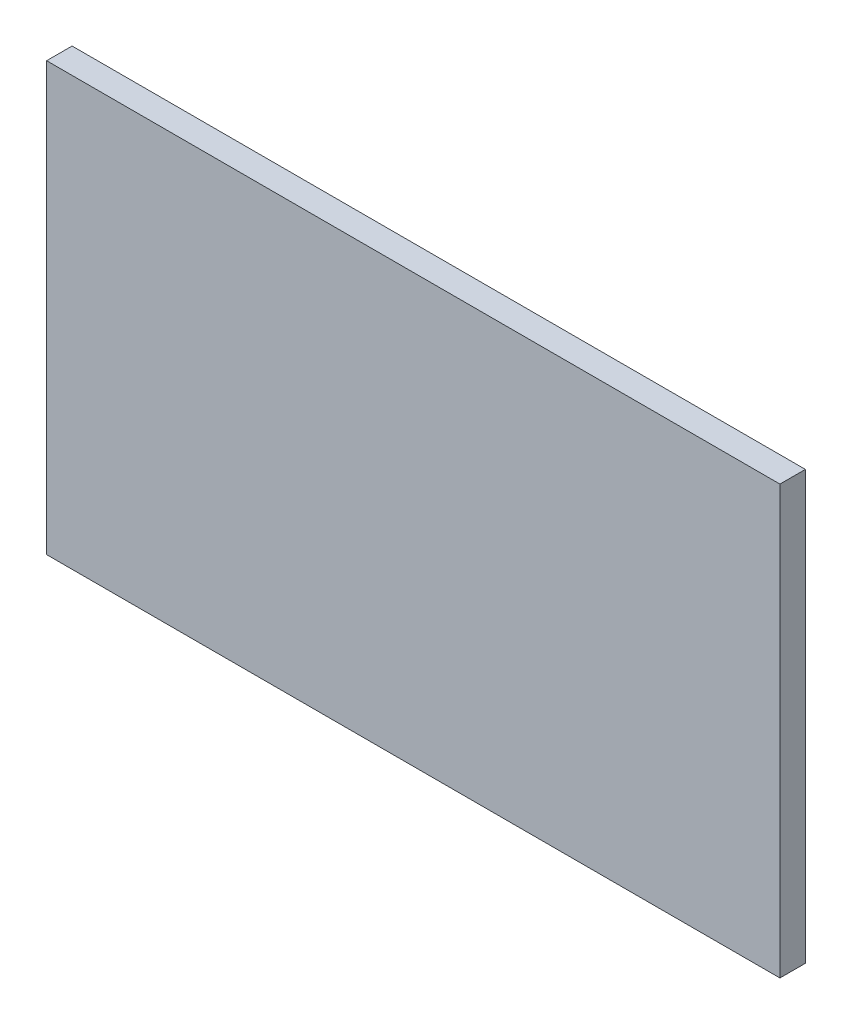
SolidWorks part; units mm, degrees
ref_plane "Front Plane" through (0, 0, 0) normal (0, 0, 1) x (1, 0, 0)
ref_plane "Top Plane" through (0, 0, 0) normal (0, 1, 0) x (1, 0, 0)
ref_plane "Right Plane" through (0, 0, 0) normal (1, 0, 0) x (0, 0, -1)
sketch "Sketch1" plane through (0, 0, 0) normal (0, 0, 1) x (1, 0, 0)
  line L1 (0, 0) -> (1440, 0)
  line L2 (0, 0) -> (0, 840)
  line L3 (0, 840) -> (1440, 840)
  line L4 (1440, 0) -> (1440, 840)
  dimension "D1" = 840
  dimension "D2" = 1440
extrude "Boss-Extrude1" add sketch "Sketch1" along normal blind 50
